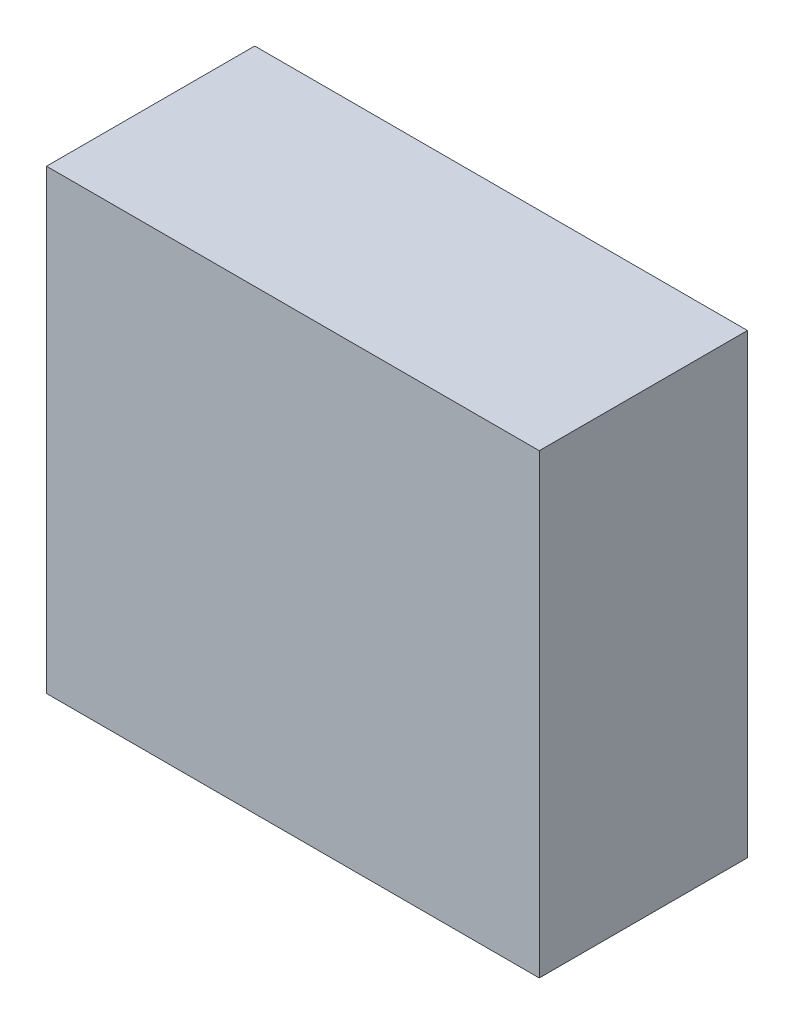
SolidWorks part; units mm, degrees
ref_plane "Front Plane" through (0, 0, 0) normal (0, 0, 1) x (1, 0, 0)
ref_plane "Top Plane" through (0, 0, 0) normal (0, 1, 0) x (1, 0, 0)
ref_plane "Right Plane" through (0, 0, 0) normal (1, 0, 0) x (0, 0, -1)
sketch "Sketch1" plane through (0, 0, 0) normal (0, 0, 1) x (1, 0, 0)
  line L1 (-90.17, 83.566) -> (90.17, 83.566)
  line L2 (-90.17, 83.566) -> (-90.17, -83.566)
  line L3 (-90.17, -83.566) -> (90.17, -83.566)
  line L4 (90.17, 83.566) -> (90.17, -83.566)
  line L5 (-90.17, 83.566) -> (90.17, -83.566) construction
  line L6 (-90.17, -83.566) -> (90.17, 83.566) construction
  point P0 (0, 0)
  dimension "D1" = 180.34
  dimension "D2" = 167.132
extrude "Boss-Extrude1" add sketch "Sketch1" along normal mid plane 76.2
